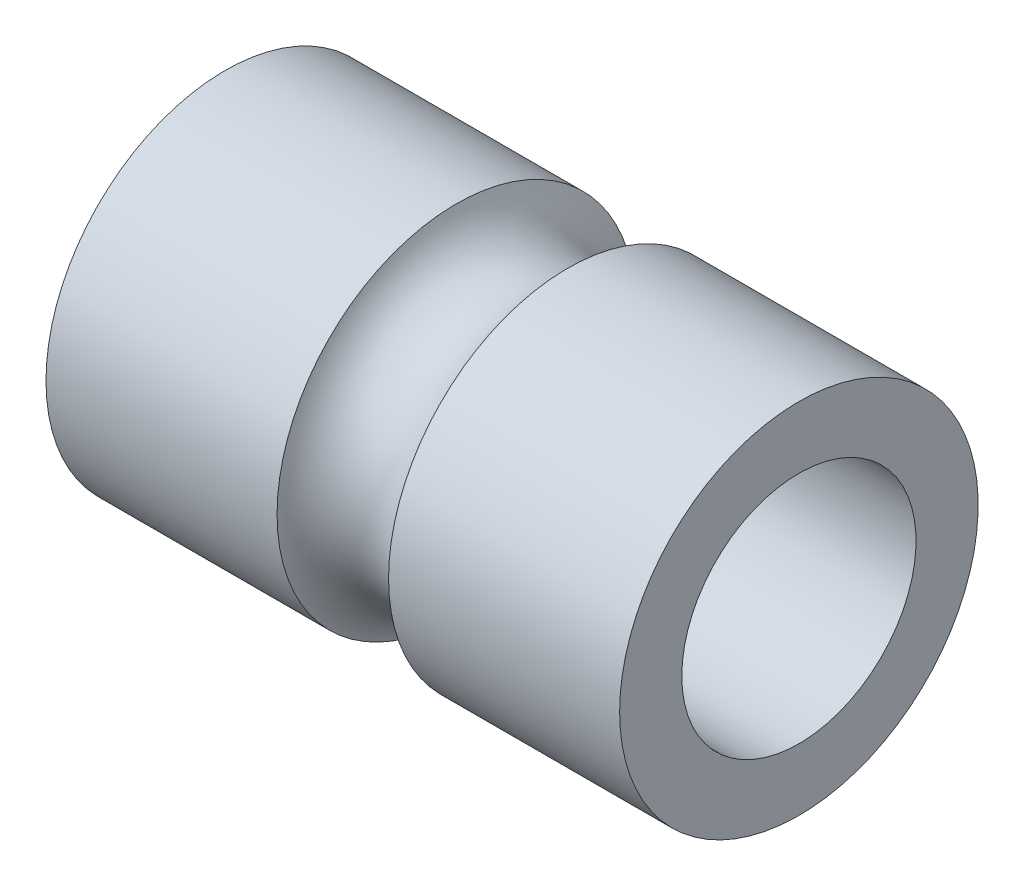
SolidWorks part; units mm, degrees
material "Brass"
ref_plane "Front Plane" through (0, 0, 0) normal (0, 0, 1) x (1, 0, 0)
ref_plane "Top Plane" through (0, 0, 0) normal (0, 1, 0) x (1, 0, 0)
ref_plane "Right Plane" through (0, 0, 0) normal (1, 0, 0) x (0, 0, -1)
sketch "Sketch1" plane through (0, 0, 0) normal (0, 0, 1) x (1, 0, 0)
  line L0 (-1000, 0) -> (49000, 0) construction
  line L1 (0, -1000) -> (0, 49000) construction
  line L2 (0, 2.45) -> (12, 2.45)
  line L3 (12, 2.45) -> (12, 3.75)
  line L4 (12, 3.75) -> (7.1662, 3.75)
  line L7 (0, 3.75) -> (0, 2.45)
  line L8 (0, 2.45) -> (0.0195, 2.4565)
  line L11 (4.8338, 3.75) -> (0, 3.75)
  line L12 (6, 4.2) -> (6, 2.1213) construction
  line L13 (6, 2.95) -> (13.015, 2.95) construction
  arc A0 (4.8338, 3.75) -> (7.1662, 3.75) centre (6, 4.2) ccw
  dimension "D7" = 2.5
  dimension "D2" = 12
  dimension "D4" = 7.5
  dimension "D5" = 4.9
  dimension "D6" = 6
  dimension "D8" = 0.5
revolve "Revolve4" add sketch "Sketch1" angle 360 about L0
